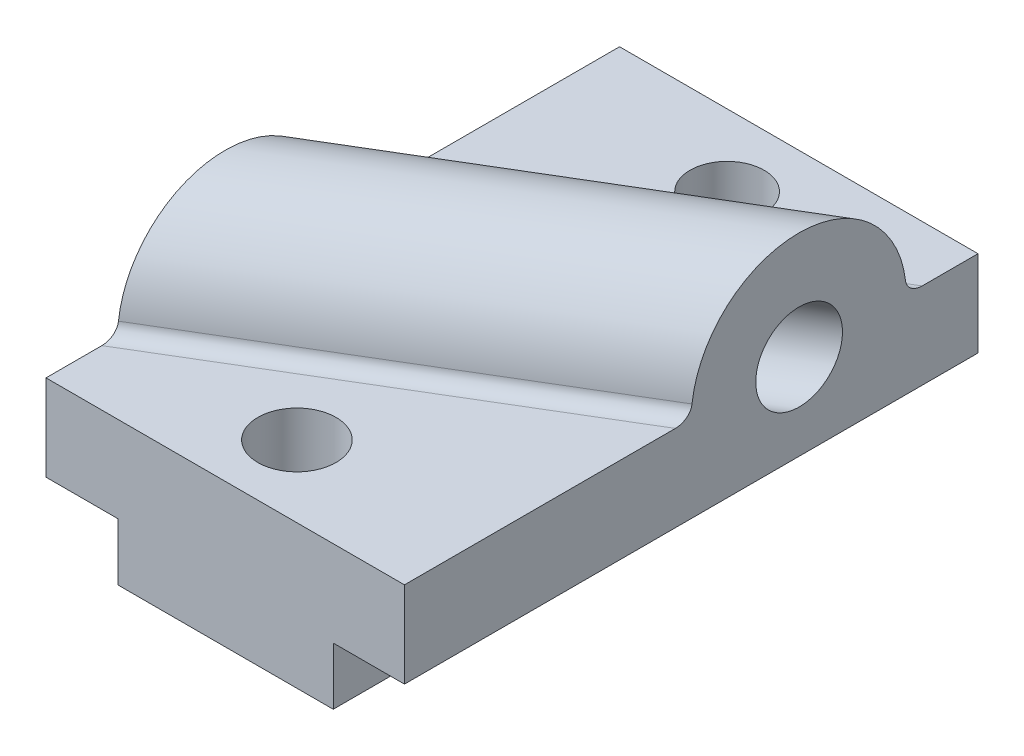
SolidWorks part; units mm, degrees
ref_plane "Ön Düzlem" through (0, 0, 0) normal (0, 0, 1) x (1, 0, 0)
ref_plane "Üst Düzlem" through (0, 0, 0) normal (0, 1, 0) x (1, 0, 0)
ref_plane "Sağ Düzlem" through (0, 0, 0) normal (1, 0, 0) x (0, 0, -1)
sketch "Çizim2" plane through (0, 0, 0) normal (0, 1, 0) x (1, 0, 0)
  line L1 (-3.3755, 40.2337) -> (46.6245, 40.2337)
  line L2 (-3.3755, 40.2337) -> (-3.3755, -39.7663)
  line L3 (-3.3755, -39.7663) -> (46.6245, -39.7663)
  line L4 (46.6245, 40.2337) -> (46.6245, -39.7663)
  dimension "D1" = 80
  dimension "D2" = 50
extrude "Yükseklik-Ekstrüzyon1" add sketch "Çizim2" along normal blind 12
sketch "Çizim3" plane through (0, 12, 0) normal (0, 1, 0) x (1, 0, 0)
  line L0 (46.6245, 40.2337) -> (46.6245, 15.2337) construction
  line L1 (46.6245, -39.7663) -> (46.6245, 40.2337) construction
  line L2 (-3.3755, -39.7663) -> (-3.3755, -14.7663) construction
  line L3 (-3.3755, 40.2337) -> (-3.3755, -39.7663) construction
  line L5 (-3.3755, -14.7663) -> (46.6245, 15.2337) construction
sketch "Çizim5" plane through (0, 12, 0) normal (0, 1, 0) x (1, 0, 0)
  line L0 (-3.3755, -14.7663) -> (46.6245, 15.2337) construction
  line L1 (-3.3755, 40.2337) -> (-3.3755, -39.7663) construction
  line L2 (46.6245, -39.7663) -> (46.6245, 40.2337) construction
  dimension "D1" = 25
  dimension "D2" = 25
sketch "Çizim9" plane through (46.6245, 0, 0) normal (1, 0, 0) x (0, 0, -1)
  line L0 (40.2337, 12) -> (15.2337, 12) construction
  circle A0 centre (15.2823, 12) radius 6.0486
sketch "Çizim7" plane through (0, 0, 0) normal (0, -1, 0) x (1, 0, 0)
  line L0 (36.6916, 39.7663) -> (6.6916, 39.7663)
  line L1 (-3.3755, 39.7663) -> (46.6245, 39.7663) construction
  line L2 (6.6916, -40.2337) -> (36.6916, -40.2337)
  line L3 (46.6245, -40.2337) -> (-3.3755, -40.2337) construction
  line L4 (6.6916, 39.7663) -> (6.6916, -40.2337)
  line L5 (36.6916, 39.7663) -> (36.6916, -40.2337)
  point P5 (21.6916, 39.7663)
  point P10 (21.6916, -40.2337)
extrude "Yükseklik-Ekstrüzyon2" add sketch "Çizim7" along normal blind 8
sketch "Çizim8" plane through (46.6245, 0, 0) normal (1, 0, 0) x (0, 0, -1)
  line L0 (40.2337, 12) -> (15.2337, 12) construction
  line L1 (40.2337, 12) -> (-16.5735, 12) construction
  line L2 (-39.7663, 12) -> (40.2337, 12) construction
  arc A0 (30.2337, 12) -> (0.2337, 12) centre (15.2337, 12) ccw
  circle A1 centre (15.2337, 12) radius 6
  line M3 (40.2337, 12) -> (-39.7663, 12)
  dimension "D1" = 15
  dimension "D2" = 6
extrude "Yükseklik-Ekstrüzyon3" add sketch "Çizim8" along direction (0.8575, 0, -0.5145) on the side against the normal up to surface (50 mm away) contours A1 A0 M3
extrude "Kes-Ekstrüzyon2" cut sketch "Çizim9" along direction (0.8575, 0, -0.5145) on the side against the normal blind 69 contours A0
fillet "Radyus1" radius 2 2 edges at (21.6245, 12, 14.7663) (21.6245, 12, -15.2337)
sketch "Çizim10" plane through (0, 12, 0) normal (0, 1, 0) x (1, 0, 0)
  line L0 (46.6245, 40.2337) -> (-3.3755, 40.2337) construction
  line L1 (-3.3755, -39.7663) -> (46.6245, -39.7663) construction
  circle A0 centre (21.6245, -29.7663) radius 5.458
  circle A1 centre (21.6245, 30.2337) radius 5.1717
  dimension "D1" = 60
  dimension "D2" = 10
  dimension "D3" = 10
extrude "Kes-Ekstrüzyon3" cut sketch "Çizim10" against normal blind 69
